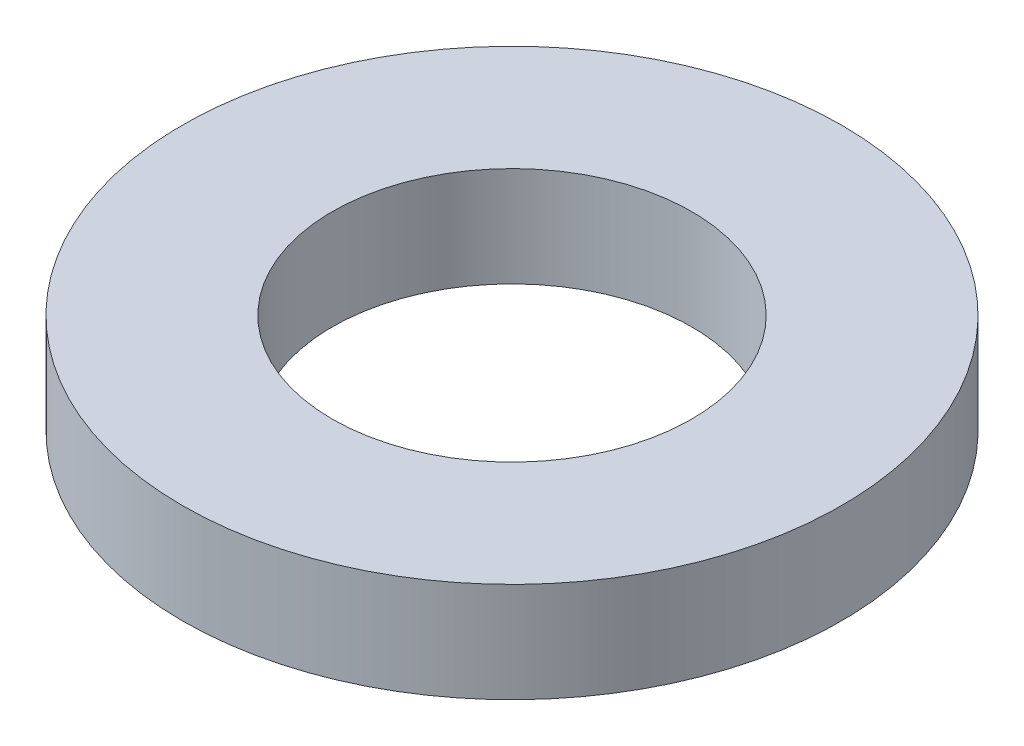
SolidWorks part; units mm, degrees
ref_plane "Front Plane" through (0, 0, 0) normal (0, 0, 1) x (1, 0, 0)
ref_plane "Top Plane" through (0, 0, 0) normal (0, 1, 0) x (1, 0, 0)
ref_plane "Right Plane" through (0, 0, 0) normal (1, 0, 0) x (0, 0, -1)
sketch "Sketch1" plane through (0, 0, 0) normal (0, 1, 0) x (1, 0, 0)
  circle A0 centre (0, 0) radius 1.8
  circle A1 centre (0, 0) radius 3.3
  dimension "D1" = 3.6
  dimension "D2" = 1.5
extrude "Boss-Extrude1" add sketch "Sketch1" along normal blind 1
